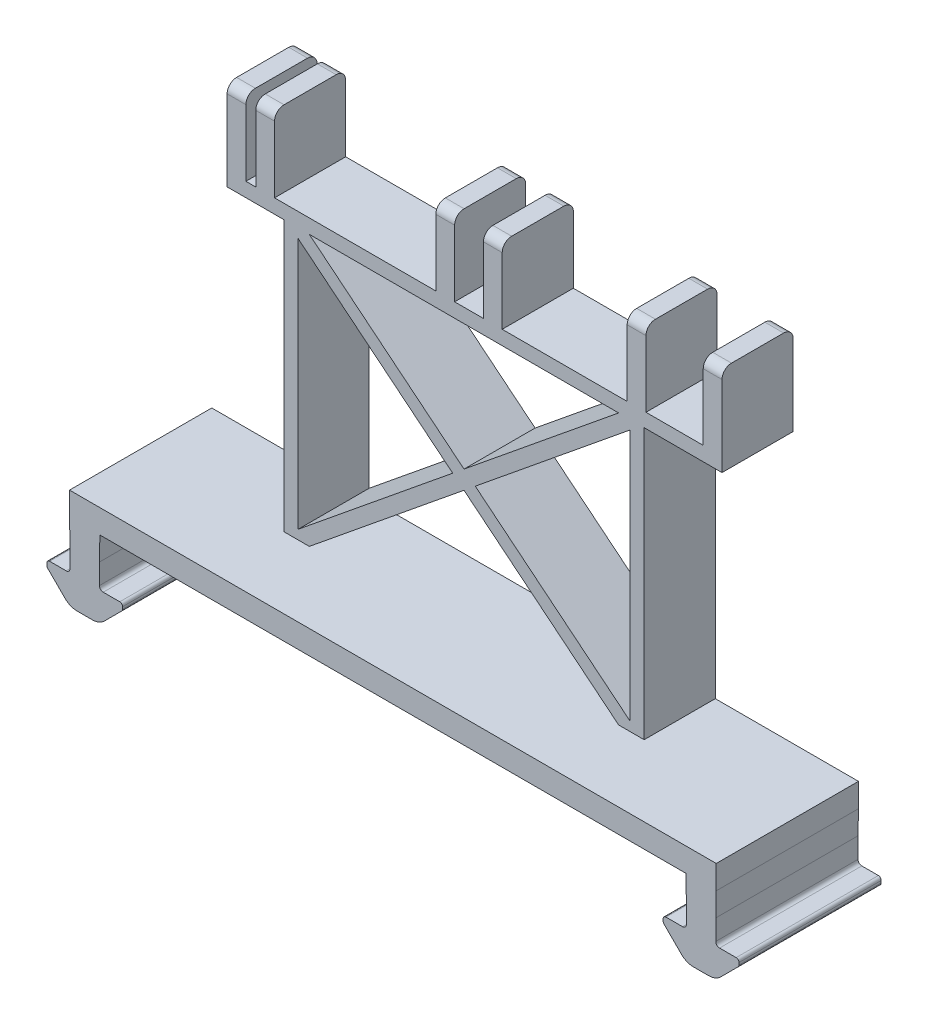
SolidWorks part; units mm, degrees
ref_plane "Front Plane" through (0, 0, 0) normal (0, 0, 1) x (1, 0, 0)
ref_plane "Top Plane" through (0, 0, 0) normal (0, 1, 0) x (1, 0, 0)
ref_plane "Right Plane" through (0, 0, 0) normal (1, 0, 0) x (0, 0, -1)
sketch "Sketch1" plane through (0, 0, 0) normal (0, 0, 1) x (1, 0, 0)
  line L7 (0, 0) -> (0, 26.663) construction
  line L8 (-2.0169, 6.858) -> (2.0169, 6.858)
  line L9 (5.3755, 8.2492) -> (10.0266, 12.9003)
  line L10 (10.287, 13.5289) -> (10.287, 14.0979)
  line L11 (9.398, 14.9869) -> (4.953, 14.9869)
  line L12 (4.064, 15.8759) -> (4.064, 27.6869)
  line L13 (0, 0) -> (20.2214, 20.2214) construction
  line L14 (-4.064, 15.8759) -> (-4.064, 27.6869)
  line L15 (-9.398, 14.9869) -> (-4.953, 14.9869)
  line L16 (-10.287, 13.5289) -> (-10.287, 14.0979)
  line L17 (-5.3755, 8.2492) -> (-10.0266, 12.9003)
  line L19 (163.0831, 6.858) -> (167.1169, 6.858)
  line L20 (170.4755, 8.2492) -> (175.1266, 12.9003)
  line L21 (175.387, 13.5289) -> (175.387, 14.0979)
  line L22 (174.498, 14.9869) -> (170.053, 14.9869)
  line L23 (169.164, 15.8759) -> (169.164, 27.6869)
  line L24 (161.036, 15.8759) -> (161.036, 27.6869)
  line L25 (155.702, 14.9869) -> (160.147, 14.9869)
  line L26 (154.813, 13.5289) -> (154.813, 14.0979)
  line L27 (159.7245, 8.2492) -> (155.0734, 12.9003)
  line L29 (-4.064, 27.6869) -> (-4.064, 34.0369)
  line L30 (-4.064, 34.0369) -> (169.164, 34.0369)
  line L31 (169.164, 34.0369) -> (169.164, 27.6869)
  line L32 (4.064, 27.6869) -> (161.036, 27.6869)
  arc A0 (10.0266, 12.9003) -> (10.287, 13.5289) centre (9.398, 13.5289) ccw
  arc A1 (9.398, 14.9869) -> (10.287, 14.0979) centre (9.398, 14.0979) cw
  arc A2 (4.953, 14.9869) -> (4.064, 15.8759) centre (4.953, 15.8759) cw
  arc A3 (2.0169, 6.858) -> (5.3755, 8.2492) centre (2.0169, 11.6078) ccw
  arc A4 (-2.0169, 6.858) -> (-5.3755, 8.2492) centre (-2.0169, 11.6078) cw
  arc A5 (-4.953, 14.9869) -> (-4.064, 15.8759) centre (-4.953, 15.8759) ccw
  arc A6 (-9.398, 14.9869) -> (-10.287, 14.0979) centre (-9.398, 14.0979) ccw
  arc A7 (-10.0266, 12.9003) -> (-10.287, 13.5289) centre (-9.398, 13.5289) cw
  arc A8 (175.1266, 12.9003) -> (175.387, 13.5289) centre (174.498, 13.5289) ccw
  arc A9 (174.498, 14.9869) -> (175.387, 14.0979) centre (174.498, 14.0979) cw
  arc A10 (170.053, 14.9869) -> (169.164, 15.8759) centre (170.053, 15.8759) cw
  arc A11 (167.1169, 6.858) -> (170.4755, 8.2492) centre (167.1169, 11.6078) ccw
  arc A12 (163.0831, 6.858) -> (159.7245, 8.2492) centre (163.0831, 11.6078) cw
  arc A13 (160.147, 14.9869) -> (161.036, 15.8759) centre (160.147, 15.8759) ccw
  arc A14 (155.702, 14.9869) -> (154.813, 14.0979) centre (155.702, 14.0979) ccw
  arc A15 (155.0734, 12.9003) -> (154.813, 13.5289) centre (155.702, 13.5289) cw
  point P1 (-4.064, 14.9869)
  point P20 (4.064, 14.9869)
  point P34 (0, 6.858)
  point P36 (161.036, 14.9869)
  point P63 (165.1, 6.858)
  dimension "D6" = 0.889
  dimension "D9" = 4.7498
  dimension "D1" = 12.7
  dimension "D2" = 4.064
  dimension "D3" = 6.858
  dimension "D4" = 10.287
  dimension "D5" = 2.032
  dimension "D7" = 0.569
  dimension "D8" = 45
  dimension "D11" = 165.1
  dimension "D12" = 6.35
  dimension "D10" = 2
extrude "Boss-Extrude2" add sketch "Sketch1" along normal blind 38.1
sketch "Sketch7" plane through (0, 0, 0) normal (0, 0, 1) x (1, 0, 0)
  line L0 (82.55, 68.2701) -> (82.55, 42.7511) construction
  line L1 (130.81, 106.4269) -> (169.164, 106.4269)
  line L3 (169.164, 34.0369) -> (-4.064, 34.0369) construction
  line L4 (-4.064, 34.0369) -> (-4.064, 15.8759) construction
  line L6 (34.29, 106.4269) -> (34.29, 34.0369)
  line L7 (34.29, 34.0369) -> (38.1, 34.0369)
  line L8 (130.81, 106.4269) -> (130.81, 34.0369)
  line L9 (-4.064, 110.2369) -> (169.164, 110.2369)
  line L10 (-4.064, 110.2369) -> (-4.064, 106.4269)
  line L11 (-4.064, 106.4269) -> (34.29, 106.4269)
  line L12 (169.164, 110.2369) -> (169.164, 106.4269)
  line L13 (38.1, 34.0369) -> (38.1, 106.4269)
  line L14 (127, 106.4269) -> (127, 34.0369)
  line L15 (38.1, 106.4269) -> (127, 106.4269)
  line L16 (127, 34.0369) -> (130.81, 34.0369)
  point P4 (82.55, 34.0369)
  point P15 (82.55, 110.2369)
  point P21 (0, 0)
  dimension "D1" = 72.39
  dimension "D2" = 3.81
  dimension "D3" = 3.81
  dimension "D4" = 44.45
extrude "Boss-Extrude6" add sketch "Sketch7" along normal blind 19.05
sketch "Sketch6" plane through (0, 110.2369, 0) normal (0, 1, 0) x (1, 0, 0)
  line L1 (19.1008, 0) -> (24.1808, 0)
  line L2 (19.1008, 0) -> (19.1008, -19.05)
  line L3 (19.1008, -19.05) -> (24.1808, -19.05)
  line L4 (24.1808, 0) -> (24.1808, -19.05)
  line L24 (169.164, 0) -> (130.81, 0) construction
  line L25 (26.7208, 0) -> (26.7208, -19.05)
  line L26 (-4.064, -38.1) -> (-4.064, 0) construction
  line L27 (26.7208, -19.05) -> (31.8008, -19.05)
  line L28 (31.8008, 0) -> (31.8008, -19.05)
  line L29 (26.7208, 0) -> (31.8008, 0)
  line L30 (75.0062, 0) -> (75.0062, -19.05)
  line L31 (75.0062, -19.05) -> (80.0862, -19.05)
  line L32 (80.0862, 0) -> (80.0862, -19.05)
  line L33 (75.0062, 0) -> (80.0862, 0)
  line L34 (87.7062, 0) -> (87.7062, -19.05)
  line L35 (87.7062, -19.05) -> (92.7862, -19.05)
  line L36 (92.7862, 0) -> (92.7862, -19.05)
  line L37 (87.7062, 0) -> (92.7862, 0)
  line L38 (126.2634, 0) -> (126.2634, -19.05)
  line L39 (126.2634, -19.05) -> (131.3434, -19.05)
  line L40 (131.3434, 0) -> (131.3434, -19.05)
  line L41 (126.2634, 0) -> (131.3434, 0)
  line L42 (146.5834, 0) -> (146.5834, -19.05)
  line L43 (146.5834, -19.05) -> (151.6634, -19.05)
  line L44 (151.6634, 0) -> (151.6634, -19.05)
  line L45 (146.5834, 0) -> (151.6634, 0)
  line L46 (-4.064, -38.1) -> (-4.064, 0) construction
  point P5 (0, 0)
  point P8 (0, 0)
  dimension "D1" = 5.08
  dimension "D2" = 19.05
  dimension "D4" = 28.2448
  dimension "D5" = 5.08
  dimension "D6" = 5.08
  dimension "D3" = 5.08
  dimension "D7" = 5.08
  dimension "D8" = 5.08
  dimension "D9" = 30.7848
  dimension "D10" = 84.1502
  dimension "D11" = 91.7702
  dimension "D12" = 150.6474
  dimension "D13" = 135.4074
extrude "Boss-Extrude5" add sketch "Sketch6" along normal blind 20.32
sketch "Sketch10" plane through (0, 0, 0) normal (0, 0, 1) x (1, 0, 0)
  line L1 (19.1008, 110.2369) -> (-4.064, 110.2369)
  line L2 (19.1008, 110.2369) -> (19.1008, 106.4269)
  line L3 (19.1008, 106.4269) -> (-4.064, 106.4269)
  line L4 (-4.064, 110.2369) -> (-4.064, 106.4269)
  line L5 (151.6634, 110.2369) -> (169.164, 110.2369)
  line L6 (151.6634, 110.2369) -> (151.6634, 106.4269)
  line L7 (151.6634, 106.4269) -> (169.164, 106.4269)
  line L8 (169.164, 110.2369) -> (169.164, 106.4269)
extrude "Cut-Extrude3" cut sketch "Sketch10" along normal up to surface (19.05 mm away) up to face at (82.6968, 107.9085, 19.05)
fillet "Fillet1" radius 2.54 12 edges at (149.1234, 130.5569, 0) (128.8034, 130.5569, 0) (149.1234, 130.5569, 19.05) (128.8034, 130.5569, 19.05) (90.2462, 130.5569, 0) (90.2462, 130.5569, 19.05) (77.5462, 130.5569, 19.05) (77.5462, 130.5569, 0) (29.2608, 130.5569, 0) (21.6408, 130.5569, 0) (21.6408, 130.5569, 19.05) (29.2608, 130.5569, 19.05)
sketch "Sketch11" plane through (0, 0, 0) normal (0, 0, 1) x (1, 0, 0)
  line L0 (38.1, 103.9702) -> (79.533, 70.2319)
  line L1 (38.1, 34.0369) -> (38.1, 106.4269) construction
  line L2 (169.164, 34.0369) -> (-4.064, 34.0369) construction
  line L3 (123.983, 34.0369) -> (127, 34.0369)
  line L4 (127, 34.0369) -> (127, 36.4936)
  line L5 (127, 106.4269) -> (127, 34.0369) construction
  line L6 (127, 36.4936) -> (85.567, 70.2319)
  line L7 (38.1, 106.4269) -> (127, 106.4269) construction
  line L8 (41.117, 106.4269) -> (38.1, 106.4269)
  line L9 (38.1, 106.4269) -> (38.1, 103.9702)
  line L10 (123.983, 106.4269) -> (127, 106.4269)
  line L11 (127, 106.4269) -> (127, 103.9702)
  line L12 (127, 103.9702) -> (85.567, 70.2319)
  line L13 (41.117, 34.0369) -> (38.1, 34.0369)
  line L14 (38.1, 34.0369) -> (38.1, 36.4936)
  line L15 (38.1, 36.4936) -> (79.533, 70.2319)
  line L16 (38.1, 34.0369) -> (127, 106.4269) construction
  line L17 (38.1, 106.4269) -> (127, 34.0369) construction
  line L18 (82.55, 67.7752) -> (41.117, 34.0369)
  line L19 (82.55, 67.7752) -> (123.983, 34.0369)
  line L20 (82.55, 72.6886) -> (123.983, 106.4269)
  line L21 (82.55, 72.6886) -> (41.117, 106.4269)
  point P18 (127, 34.0369)
  point P23 (127, 34.0369)
  point P24 (0, 0)
  dimension "D1" = 3.81
  dimension "D2" = 3.81
extrude "Boss-Extrude7" add sketch "Sketch11" along normal up to surface (19.05 mm away) up to face at (82.7151, 106.665, 19.05)
sketch "Sketch3" plane through (0, 0, 38.1) normal (0, 0, 1) x (1, 0, 0)
  line L27 (-3.937, 21.3369) -> (3.937, 21.3369) construction
  line L28 (4.064, 27.6869) -> (3.937, 21.3369)
  line L29 (-4.064, 27.6869) -> (-3.937, 21.3369)
  line L40 (-4.064, 34.0369) -> (-4.064, 15.8759) construction
  line L41 (-1004.064, 27.6869) -> (4.064, 27.6869) construction
  line L42 (161.036, 27.6869) -> (161.163, 21.3369)
  line L43 (169.164, 27.6869) -> (169.037, 21.3369)
  line L44 (169.164, 15.8759) -> (169.164, 34.0369) construction
  line L57 (5.2857, 8.339) -> (9.9368, 12.9901)
  line L58 (10.16, 13.5289) -> (10.16, 14.0979)
  line L59 (9.398, 14.8599) -> (4.953, 14.8599)
  line L61 (3.937, 15.8759) -> (3.937, 27.8139)
  line L62 (3.937, 27.8139) -> (161.163, 27.8139)
  line L66 (161.163, 27.8139) -> (161.163, 15.8759)
  line L67 (160.147, 14.8599) -> (155.702, 14.8599)
  line L68 (154.94, 14.0979) -> (154.94, 13.5289)
  line L69 (155.1632, 12.9901) -> (159.8143, 8.339)
  line L80 (163.0831, 6.985) -> (167.1169, 6.985)
  line L81 (170.3857, 8.339) -> (175.0368, 12.9901)
  line L82 (175.26, 13.5289) -> (175.26, 14.0979)
  line L85 (174.498, 14.8599) -> (170.053, 14.8599)
  line L86 (169.037, 15.8759) -> (169.037, 33.9099)
  line L91 (169.037, 33.9099) -> (-3.937, 33.9099)
  line L93 (-3.937, 33.9099) -> (-3.937, 15.8759)
  line L95 (-4.953, 14.8599) -> (-9.398, 14.8599)
  line L97 (-10.16, 14.0979) -> (-10.16, 13.5289)
  line L99 (-9.9368, 12.9901) -> (-5.2857, 8.339)
  line L101 (-2.0169, 6.985) -> (2.0169, 6.985)
  line L103 (5.2857, 8.339) -> (9.9368, 12.9901)
  line L105 (10.16, 13.5289) -> (10.16, 14.0979)
  line L109 (9.398, 14.8599) -> (4.953, 14.8599)
  line L110 (3.937, 15.8759) -> (3.937, 21.3369)
  line L112 (161.163, 21.3369) -> (161.163, 15.8759)
  line L113 (160.147, 14.8599) -> (155.702, 14.8599)
  line L114 (154.94, 14.0979) -> (154.94, 13.5289)
  line L115 (155.1632, 12.9901) -> (159.8143, 8.339)
  line L116 (163.0831, 6.985) -> (167.1169, 6.985)
  line L117 (170.3857, 8.339) -> (175.0368, 12.9901)
  line L118 (175.26, 13.5289) -> (175.26, 14.0979)
  line L119 (174.498, 14.8599) -> (170.053, 14.8599)
  line L120 (169.037, 15.8759) -> (169.037, 21.3369)
  line L122 (-3.937, 21.3369) -> (-3.937, 15.8759)
  line L123 (-4.953, 14.8599) -> (-9.398, 14.8599)
  line L124 (-10.16, 14.0979) -> (-10.16, 13.5289)
  line L125 (-9.9368, 12.9901) -> (-5.2857, 8.339)
  line L126 (-2.0169, 6.985) -> (2.0169, 6.985)
  line L137 (161.036, 27.6869) -> (1318.008, 27.6869) construction
  line L138 (19.1008, 130.5569) -> (24.1808, 130.5569) construction
  line L139 (24.13, 130.5569) -> (26.7716, 130.5569)
  line L140 (24.13, 130.5569) -> (24.13, 110.2369)
  line L141 (24.13, 110.2369) -> (26.7716, 110.2369)
  line L142 (26.7716, 130.5569) -> (26.7716, 110.2369)
  line L143 (126.2634, 130.5569) -> (131.3434, 130.5569) construction
  line L144 (80.0354, 130.5569) -> (87.757, 130.5569)
  line L145 (80.0354, 130.5569) -> (80.0354, 110.2369)
  line L146 (80.0354, 110.2369) -> (87.757, 110.2369)
  line L147 (87.757, 130.5569) -> (87.757, 110.2369)
  line L148 (131.2926, 130.5569) -> (146.6342, 130.5569)
  line L149 (131.2926, 130.5569) -> (131.2926, 110.2369)
  line L150 (131.2926, 110.2369) -> (146.6342, 110.2369)
  line L151 (146.6342, 130.5569) -> (146.6342, 110.2369)
  line L152 (126.2634, 110.2369) -> (92.7862, 110.2369) construction
  line L153 (24.1808, 128.0169) -> (24.1808, 110.2369) construction
  line L154 (26.7208, 128.0169) -> (26.7208, 110.2369) construction
  line L155 (80.0862, 128.0169) -> (80.0862, 110.2369) construction
  line L156 (87.7062, 128.0169) -> (87.7062, 110.2369) construction
  line L157 (5.3755, 8.2492) -> (10.0266, 12.9003)
  line L158 (10.287, 13.5289) -> (10.287, 14.0979)
  line L159 (9.398, 14.9869) -> (4.953, 14.9869)
  line L160 (4.064, 15.8759) -> (4.064, 27.6869)
  line L161 (4.064, 27.6869) -> (161.036, 27.6869)
  line L162 (161.036, 27.6869) -> (161.036, 15.8759)
  line L163 (160.147, 14.9869) -> (155.702, 14.9869)
  line L164 (154.813, 14.0979) -> (154.813, 13.5289)
  line L165 (155.0734, 12.9003) -> (159.7245, 8.2492)
  line L166 (163.0831, 6.858) -> (167.1169, 6.858)
  line L167 (170.4755, 8.2492) -> (175.1266, 12.9003)
  line L168 (175.387, 13.5289) -> (175.387, 14.0979)
  line L169 (174.498, 14.9869) -> (170.053, 14.9869)
  line L170 (169.164, 15.8759) -> (169.164, 34.0369)
  line L171 (169.164, 34.0369) -> (-4.064, 34.0369)
  line L172 (-4.064, 34.0369) -> (-4.064, 15.8759)
  line L173 (-4.953, 14.9869) -> (-9.398, 14.9869)
  line L174 (-10.287, 14.0979) -> (-10.287, 13.5289)
  line L175 (-10.0266, 12.9003) -> (-5.3755, 8.2492)
  line L176 (-2.0169, 6.858) -> (2.0169, 6.858)
  line L177 (5.3755, 8.2492) -> (10.0266, 12.9003)
  line L178 (10.287, 13.5289) -> (10.287, 14.0979)
  line L179 (9.398, 14.9869) -> (4.953, 14.9869)
  line L180 (4.064, 15.8759) -> (4.064, 27.6869)
  line L182 (161.036, 27.6869) -> (161.036, 15.8759)
  line L183 (160.147, 14.9869) -> (155.702, 14.9869)
  line L184 (154.813, 14.0979) -> (154.813, 13.5289)
  line L185 (155.0734, 12.9003) -> (159.7245, 8.2492)
  line L186 (163.0831, 6.858) -> (167.1169, 6.858)
  line L187 (170.4755, 8.2492) -> (175.1266, 12.9003)
  line L188 (175.387, 13.5289) -> (175.387, 14.0979)
  line L189 (174.498, 14.9869) -> (170.053, 14.9869)
  line L190 (169.164, 15.8759) -> (169.164, 27.6869)
  line L192 (-4.064, 27.6869) -> (-4.064, 15.8759)
  line L193 (-4.953, 14.9869) -> (-9.398, 14.9869)
  line L194 (-10.287, 14.0979) -> (-10.287, 13.5289)
  line L195 (-10.0266, 12.9003) -> (-5.3755, 8.2492)
  line L196 (-2.0169, 6.858) -> (2.0169, 6.858)
  line L197 (87.7062, 130.5569) -> (92.7862, 130.5569) construction
  line L198 (131.3434, 128.0169) -> (131.3434, 110.2369) construction
  line L199 (146.5834, 128.0169) -> (146.5834, 110.2369) construction
  arc A96 (2.0169, 6.985) -> (5.2857, 8.339) centre (2.0169, 11.6078) ccw
  arc A97 (9.9368, 12.9901) -> (10.16, 13.5289) centre (9.398, 13.5289) ccw
  arc A98 (10.16, 14.0979) -> (9.398, 14.8599) centre (9.398, 14.0979) ccw
  arc A99 (3.937, 15.8759) -> (4.953, 14.8599) centre (4.953, 15.8759) ccw
  arc A100 (160.147, 14.8599) -> (161.163, 15.8759) centre (160.147, 15.8759) ccw
  arc A101 (155.702, 14.8599) -> (154.94, 14.0979) centre (155.702, 14.0979) ccw
  arc A102 (154.94, 13.5289) -> (155.1632, 12.9901) centre (155.702, 13.5289) ccw
  arc A103 (159.8143, 8.339) -> (163.0831, 6.985) centre (163.0831, 11.6078) ccw
  arc A104 (167.1169, 6.985) -> (170.3857, 8.339) centre (167.1169, 11.6078) ccw
  arc A105 (175.0368, 12.9901) -> (175.26, 13.5289) centre (174.498, 13.5289) ccw
  arc A106 (175.26, 14.0979) -> (174.498, 14.8599) centre (174.498, 14.0979) ccw
  arc A107 (169.037, 15.8759) -> (170.053, 14.8599) centre (170.053, 15.8759) ccw
  arc A108 (-4.953, 14.8599) -> (-3.937, 15.8759) centre (-4.953, 15.8759) ccw
  arc A109 (-9.398, 14.8599) -> (-10.16, 14.0979) centre (-9.398, 14.0979) ccw
  arc A110 (-10.16, 13.5289) -> (-9.9368, 12.9901) centre (-9.398, 13.5289) ccw
  arc A111 (-5.2857, 8.339) -> (-2.0169, 6.985) centre (-2.0169, 11.6078) ccw
  arc A112 (2.0169, 6.985) -> (5.2857, 8.339) centre (2.0169, 11.6078) ccw
  arc A113 (9.9368, 12.9901) -> (10.16, 13.5289) centre (9.398, 13.5289) ccw
  arc A114 (10.16, 14.0979) -> (9.398, 14.8599) centre (9.398, 14.0979) ccw
  arc A115 (3.937, 15.8759) -> (4.953, 14.8599) centre (4.953, 15.8759) ccw
  arc A116 (160.147, 14.8599) -> (161.163, 15.8759) centre (160.147, 15.8759) ccw
  arc A117 (155.702, 14.8599) -> (154.94, 14.0979) centre (155.702, 14.0979) ccw
  arc A118 (154.94, 13.5289) -> (155.1632, 12.9901) centre (155.702, 13.5289) ccw
  arc A119 (159.8143, 8.339) -> (163.0831, 6.985) centre (163.0831, 11.6078) ccw
  arc A120 (167.1169, 6.985) -> (170.3857, 8.339) centre (167.1169, 11.6078) ccw
  arc A121 (175.0368, 12.9901) -> (175.26, 13.5289) centre (174.498, 13.5289) ccw
  arc A122 (175.26, 14.0979) -> (174.498, 14.8599) centre (174.498, 14.0979) ccw
  arc A123 (169.037, 15.8759) -> (170.053, 14.8599) centre (170.053, 15.8759) ccw
  arc A124 (-4.953, 14.8599) -> (-3.937, 15.8759) centre (-4.953, 15.8759) ccw
  arc A125 (-9.398, 14.8599) -> (-10.16, 14.0979) centre (-9.398, 14.0979) ccw
  arc A126 (-10.16, 13.5289) -> (-9.9368, 12.9901) centre (-9.398, 13.5289) ccw
  arc A127 (-5.2857, 8.339) -> (-2.0169, 6.985) centre (-2.0169, 11.6078) ccw
  arc A144 (2.0169, 6.858) -> (5.3755, 8.2492) centre (2.0169, 11.6078) ccw
  arc A145 (10.0266, 12.9003) -> (10.287, 13.5289) centre (9.398, 13.5289) ccw
  arc A146 (10.287, 14.0979) -> (9.398, 14.9869) centre (9.398, 14.0979) ccw
  arc A147 (4.064, 15.8759) -> (4.953, 14.9869) centre (4.953, 15.8759) ccw
  arc A148 (160.147, 14.9869) -> (161.036, 15.8759) centre (160.147, 15.8759) ccw
  arc A149 (155.702, 14.9869) -> (154.813, 14.0979) centre (155.702, 14.0979) ccw
  arc A150 (154.813, 13.5289) -> (155.0734, 12.9003) centre (155.702, 13.5289) ccw
  arc A151 (159.7245, 8.2492) -> (163.0831, 6.858) centre (163.0831, 11.6078) ccw
  arc A152 (167.1169, 6.858) -> (170.4755, 8.2492) centre (167.1169, 11.6078) ccw
  arc A153 (175.1266, 12.9003) -> (175.387, 13.5289) centre (174.498, 13.5289) ccw
  arc A154 (175.387, 14.0979) -> (174.498, 14.9869) centre (174.498, 14.0979) ccw
  arc A155 (169.164, 15.8759) -> (170.053, 14.9869) centre (170.053, 15.8759) ccw
  arc A156 (-4.953, 14.9869) -> (-4.064, 15.8759) centre (-4.953, 15.8759) ccw
  arc A157 (-9.398, 14.9869) -> (-10.287, 14.0979) centre (-9.398, 14.0979) ccw
  arc A158 (-10.287, 13.5289) -> (-10.0266, 12.9003) centre (-9.398, 13.5289) ccw
  arc A159 (-5.3755, 8.2492) -> (-2.0169, 6.858) centre (-2.0169, 11.6078) ccw
  arc A160 (2.0169, 6.858) -> (5.3755, 8.2492) centre (2.0169, 11.6078) ccw
  arc A161 (10.0266, 12.9003) -> (10.287, 13.5289) centre (9.398, 13.5289) ccw
  arc A162 (10.287, 14.0979) -> (9.398, 14.9869) centre (9.398, 14.0979) ccw
  arc A163 (4.064, 15.8759) -> (4.953, 14.9869) centre (4.953, 15.8759) ccw
  arc A164 (160.147, 14.9869) -> (161.036, 15.8759) centre (160.147, 15.8759) ccw
  arc A165 (155.702, 14.9869) -> (154.813, 14.0979) centre (155.702, 14.0979) ccw
  arc A166 (154.813, 13.5289) -> (155.0734, 12.9003) centre (155.702, 13.5289) ccw
  arc A167 (159.7245, 8.2492) -> (163.0831, 6.858) centre (163.0831, 11.6078) ccw
  arc A168 (167.1169, 6.858) -> (170.4755, 8.2492) centre (167.1169, 11.6078) ccw
  arc A169 (175.1266, 12.9003) -> (175.387, 13.5289) centre (174.498, 13.5289) ccw
  arc A170 (175.387, 14.0979) -> (174.498, 14.9869) centre (174.498, 14.0979) ccw
  arc A171 (169.164, 15.8759) -> (170.053, 14.9869) centre (170.053, 15.8759) ccw
  arc A172 (-4.953, 14.9869) -> (-4.064, 15.8759) centre (-4.953, 15.8759) ccw
  arc A173 (-9.398, 14.9869) -> (-10.287, 14.0979) centre (-9.398, 14.0979) ccw
  arc A174 (-10.287, 13.5289) -> (-10.0266, 12.9003) centre (-9.398, 13.5289) ccw
  arc A175 (-5.3755, 8.2492) -> (-2.0169, 6.858) centre (-2.0169, 11.6078) ccw
  dimension "D3" = 0
  dimension "D2" = 6.35
  dimension "D4" = 0.0508
  dimension "D5" = 0.0508
  dimension "D6" = 0.0508
  dimension "D7" = 0.0508
  dimension "D8" = 0.0508
  dimension "D9" = 0.0508
  dimension "D1" = 0.127
extrude "Clearance Trim" cut sketch "Sketch3" against normal up to surface (38.1 mm away)
